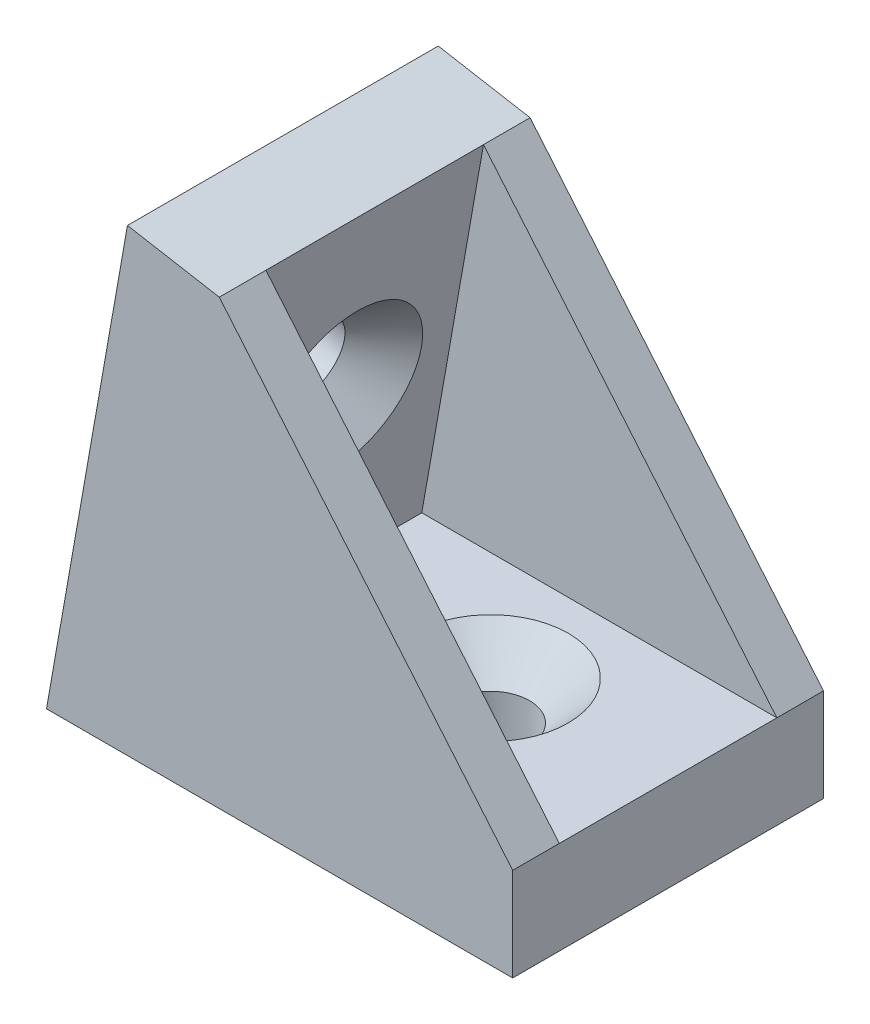
SolidWorks part; units mm, degrees
ref_plane "Top Plane" through (0, 0, 0) normal (0, 0, 1) x (1, 0, 0)
ref_plane "Right Plane" through (0, 0, 0) normal (0, 1, 0) x (1, 0, 0)
ref_plane "Front Plane" through (0, 0, 0) normal (1, 0, 0) x (0, 0, -1)
sketch "Sketch1" plane through (0, 0, 0) normal (0, 0, 1) x (1, 0, 0)
  line L0 (0, 0) -> (5.2094, 29.5442)
  line L2 (30, 0) -> (0, 0)
  line L3 (5.2094, 29.5442) -> (11.1183, 28.5023)
  line L4 (11.1183, 28.5023) -> (7.1505, 6)
  line L5 (7.1505, 6) -> (30, 6)
  line L6 (30, 6) -> (30, 0)
  dimension "D1" = 80
  dimension "D2" = 30
  dimension "D3" = 6
extrude "Boss-Extrude1" add sketch "Sketch1" along normal mid plane 20
sketch "Sketch2" plane through (0, 0, 10) normal (0, 0, 1) x (1, 0, 0)
  line L0 (11.1183, 28.5023) -> (7.1505, 6)
  line L1 (7.1505, 6) -> (30, 6)
  line L2 (30, 6) -> (11.1183, 28.5023)
extrude "Boss-Extrude2" add sketch "Sketch2" against normal blind 3
mirror "Mirror1" about plane through (0, 0, 0) normal (0, 0, 1) of "Boss-Extrude2"
sketch "Sketch3" plane through (5.9088, -1.0419, 0) normal (0.9848, -0.1736, 0) x (0, 0, -1)
  line L0 (0, 7.1505) -> (0, 30) construction
  line L1 (-7, 7.1505) -> (7, 7.1505) construction
  line L2 (-7, 30) -> (7, 30) construction
  circle A0 centre (0, 18.5753) radius 2.5
  dimension "D1" = 5
extrude "Cut-Extrude1" cut sketch "Sketch3" against normal through all
sketch "Sketch4" plane through (0, 6, 0) normal (0, 1, 0) x (1, 0, 0)
  line L0 (7.1505, 0) -> (30, 0) construction
  line L1 (7.1505, -7) -> (7.1505, 7) construction
  line L2 (30, -7) -> (30, 7) construction
  circle A0 centre (18.5753, 0) radius 2.5
  dimension "D1" = 5
extrude "Cut-Extrude2" cut sketch "Sketch4" against normal through all
chamfer "Chamfer1" distance 2.5 angle 45 2 edges at (18.5753, 6, 2.5) (9.5685, 19.7132, 0)
